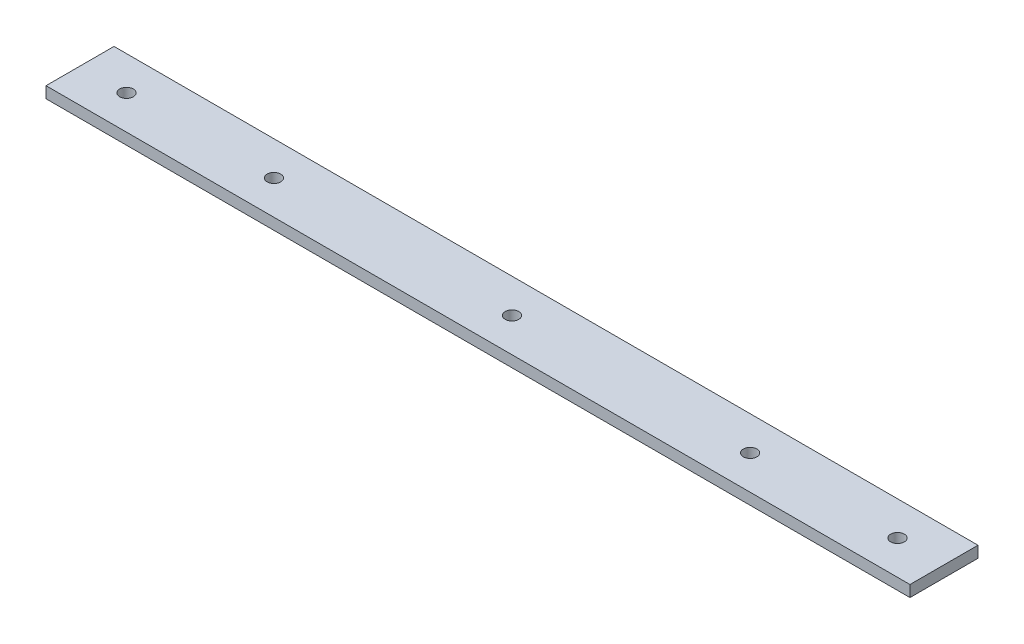
SolidWorks part; units mm, degrees
ref_plane "Front Plane" through (0, 0, 0) normal (0, 0, 1) x (1, 0, 0)
ref_plane "Top Plane" through (0, 0, 0) normal (0, 1, 0) x (1, 0, 0)
ref_plane "Right Plane" through (0, 0, 0) normal (1, 0, 0) x (0, 0, -1)
sketch "Sketch1" plane through (0, 0, 0) normal (0, 1, 0) x (1, 0, 0)
  line L0 (190.5, 67.8377) -> (190.5, -52.2363) construction
  line L1 (0, 0) -> (381, 0)
  line L2 (0, 0) -> (0, 30)
  line L3 (0, 30) -> (381, 30)
  line L4 (381, 0) -> (381, 30)
  circle A0 centre (190.5, 15) radius 3
  circle A1 centre (295.5, 15) radius 3
  circle A2 centre (360.5, 15) radius 3
  circle A3 centre (20.5, 15) radius 3
  circle A4 centre (85.5, 15) radius 3
  dimension "D3" = 6
  dimension "D5" = 105
  dimension "D7" = 6
  dimension "D8" = 6
  dimension "D1" = 381
  dimension "D2" = 30
  dimension "D4" = 190.5
  dimension "D6" = 65
extrude "Boss-Extrude1" add sketch "Sketch1" along normal blind 5
